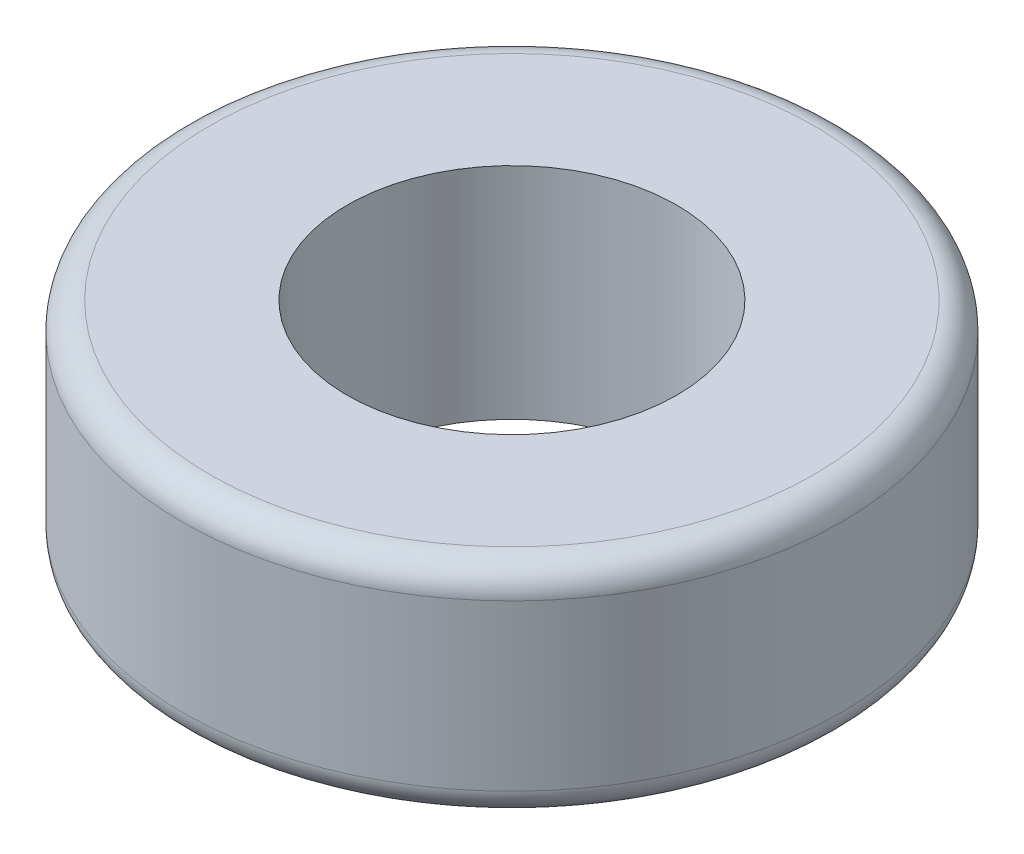
SolidWorks part; units mm, degrees
ref_plane "前视基准面" through (0, 0, 0) normal (0, 0, 1) x (1, 0, 0)
ref_plane "上视基准面" through (0, 0, 0) normal (0, 1, 0) x (1, 0, 0)
ref_plane "右视基准面" through (0, 0, 0) normal (1, 0, 0) x (0, 0, -1)
other "Configuration Table"
sketch "草图1" plane through (0, 0, 0) normal (0, 0, 1) x (1, 0, 0)
  line L0 (0, -346.4166) -> (0, 16974.411) construction
  line L1 (7.5, 3.75) -> (15, 3.75) construction
  line L2 (7.5, 5) -> (15, 5) construction
  line L3 (7.5, 5) -> (7.5, -5)
  line L4 (7.5, -5) -> (15, -5) construction
  line L5 (15, 5) -> (15, -5) construction
  line L6 (7.5, -3.75) -> (15, -3.75) construction
  line L7 (13.75, 5) -> (13.75, -5) construction
  line L8 (7.5, -5) -> (13.75, -5)
  line L9 (15, -3.75) -> (15, 3.75)
  line L10 (13.75, 5) -> (7.5, 5)
  line L11 (13.5, 3.5) -> (9, 3.5)
  line L12 (9, 3.5) -> (9, -3.5)
  line L13 (9, -3.5) -> (13.5, -3.5)
  line L14 (13.5, -3.5) -> (13.5, 3.5)
  arc A0 (15, 3.75) -> (13.75, 5) centre (13.75, 3.75) ccw
  arc A1 (13.75, -5) -> (15, -3.75) centre (13.75, -3.75) ccw
  arc A2 (13.5, -3.5) -> (13.5, -3.5) centre (13.5, -3.5) ccw
  arc A3 (13.5, 3.5) -> (13.5, 3.5) centre (13.5, 3.5) ccw
  point P7 (7.5, 0)
  dimension "D1" = 15
  dimension "D2" = 7.5
  dimension "D3" = 10
  dimension "D4" = 1.25
  dimension "D5" = 1.25
  dimension "D6" = 1.25
  dimension "D7" = 1.5
revolve "旋转3" add sketch "草图1" angle 360 about L0
